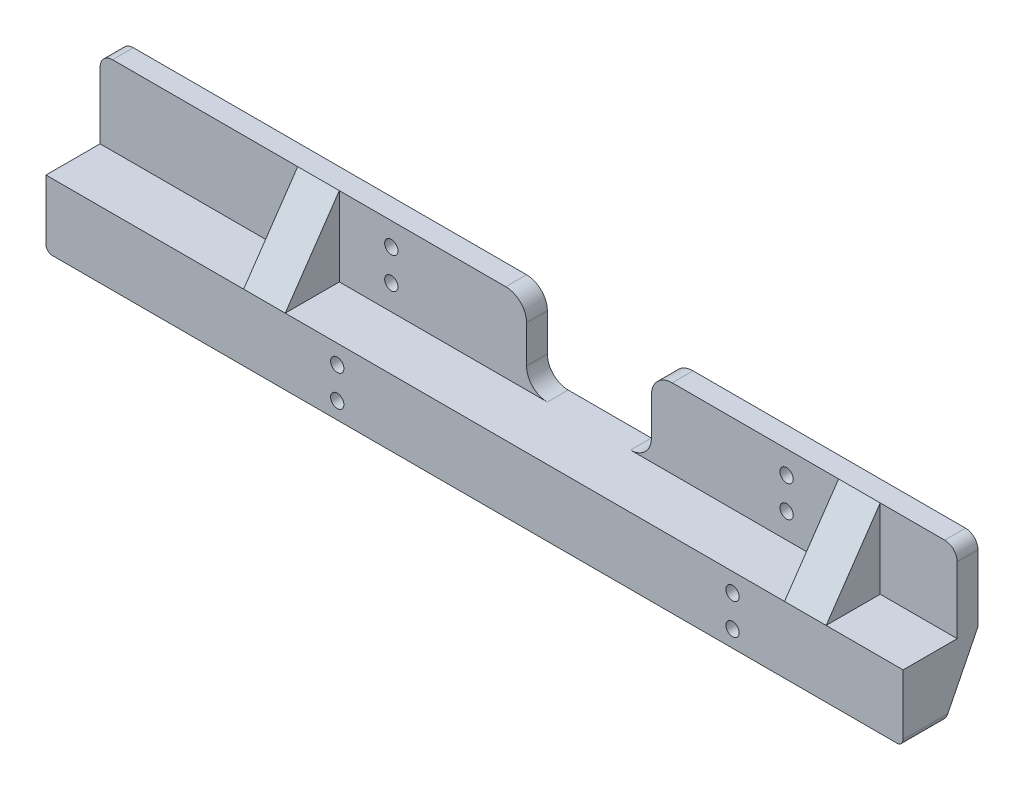
SolidWorks part; units mm, degrees
ref_plane "前视基准面" through (0, 0, 0) normal (0, 0, 1) x (1, 0, 0)
ref_plane "上视基准面" through (0, 0, 0) normal (0, 1, 0) x (1, 0, 0)
ref_plane "右视基准面" through (0, 0, 0) normal (1, 0, 0) x (0, 0, -1)
sketch "草图1" plane through (0, 0, 0) normal (0, 0, 1) x (1, 0, 0)
  line L1 (-117.5, 17.5) -> (117.5, 17.5)
  line L2 (-117.5, 17.5) -> (-117.5, -17.5)
  line L3 (-117.5, -17.5) -> (117.5, -17.5)
  line L4 (117.5, 17.5) -> (117.5, -17.5)
  line L5 (0, -17.5) -> (0, 17.5) construction
  line L6 (-117.5, 0) -> (117.5, 0) construction
  circle A1 centre (-47.5, 13.5) radius 1.6
  circle A2 centre (47.5, 13.5) radius 1.6
  circle A3 centre (-47.5, 6) radius 1.6
  circle A4 centre (47.5, 6) radius 1.6
  point P0 (0, 0)
  dimension "D1" = 95
  dimension "D4" = 4
  dimension "D5" = 3.2
  dimension "D6" = 7.5
  dimension "D2" = 35
  dimension "D3" = 235
extrude "凸台-拉伸1" add sketch "草图1" along normal blind 18
fillet "圆角1" radius 1.5 2 edges at (117.5, 17.5, 9) (-117.5, 17.5, 9)
sketch "草图2" plane through (-117.5, 0, 0) normal (-1, 0, 0) x (0, 0, 1)
  line L0 (0, 1.5) -> (8, 17.5)
  line L1 (0, 16) -> (0, -17.5) construction
  line L2 (0, 17.5) -> (18, 17.5) construction
  line L3 (8, 17.5) -> (0, 17.5)
  line L4 (0, 17.5) -> (0, 1.5)
  dimension "D1" = 16
  dimension "D2" = 8
extrude "切除-拉伸1" cut sketch "草图2" against normal through all
sketch "草图3" plane through (-117.5, 0, 0) normal (-1, 0, 0) x (0, 0, 1)
  line L0 (5, 1.5) -> (0, 1.5) construction
  line L1 (5, 1.5) -> (18, 1.5)
  line L3 (5, 1.5) -> (5, -17.5)
  line L4 (5, -17.5) -> (18, -17.5)
  line L5 (18, 1.5) -> (18, -17.5)
  dimension "D1" = 13
extrude "切除-拉伸2" cut sketch "草图3" against normal through all
sketch "草图5" plane through (0, 0, 0) normal (0, 0, -1) x (-1, 0, 0)
  line L0 (0, 0) -> (0, -50.6933) construction
  line L1 (-117.5, 1.5) -> (117.5, 1.5) construction
  line L2 (47.5, -12) -> (47.5, -4.5) construction
  line L3 (-47.5, -12) -> (-47.5, -4.5) construction
  circle A0 centre (47.5, -4.5) radius 1.6
  circle A1 centre (47.5, -12) radius 1.6
  circle A2 centre (-47.5, -12) radius 1.6
  circle A3 centre (-47.5, -4.5) radius 1.6
  dimension "D1" = 3.2
  dimension "D2" = 95
  dimension "D3" = 6
  dimension "D4" = 7.5
extrude "切除-拉伸5" cut sketch "草图5" against normal through all
sketch "草图6" plane through (0, 0, 0) normal (0, 0, -1) x (-1, 0, 0)
  circle A0 centre (47.5, 6) radius 3
  circle A1 centre (47.5, 13.5) radius 3
  circle A2 centre (-47.5, 6) radius 3
  circle A3 centre (-47.5, 13.5) radius 3
  dimension "D1" = 6
extrude "切除-拉伸6" cut sketch "草图6" against normal blind 10
sketch "草图7" plane through (0, 0, 5) normal (0, 0, 1) x (1, 0, 0)
  line L0 (117.5, -17.5) -> (-117.5, -17.5) construction
  line L1 (35, -7.5) -> (-35, -7.5)
  line L2 (35, -7.5) -> (35, -17.5)
  line L3 (35, -17.5) -> (-35, -17.5)
  line L4 (-35, -7.5) -> (-35, -17.5)
  line L5 (0, -17.5) -> (0, -7.5) construction
  line L6 (35, -12.5) -> (-35, -12.5) construction
  point P0 (0, -12.5)
  dimension "D1" = 70
  dimension "D2" = 10
extrude "切除-拉伸7" [suppressed] cut sketch "草图7" against normal through all
sketch "草图10" plane through (0, 0, 0) normal (0, 0, -1) x (-1, 0, 0)
  line L6 (117.5, -17.5) -> (-117.5, -17.5) construction
  line L7 (-88.5, -17.5) -> (-117.5, -17.5)
  line L8 (-88.5, -17.5) -> (-88.5, 17.5)
  line L9 (-88.5, 17.5) -> (-117.5, 17.5)
  line L10 (-117.5, -17.5) -> (-117.5, 17.5)
  line L11 (-116, 17.5) -> (116, 17.5) construction
  line L12 (-117.5, -17.5) -> (-117.5, 1.5) construction
  dimension "D1" = 29
extrude "切除-拉伸9" cut sketch "草图10" against normal blind 30
fillet "圆角2" radius 3 2 edges at (-117.5, -17.5, 2.5) (88.5, -17.5, 2.5)
fillet "圆角5" radius 1.5 1 edges at (88.5, 17.5, 13)
sketch "草图11" plane through (0, 0, 0) normal (0, 0, -1) x (-1, 0, 0)
  line L0 (114.5, -17.5) -> (-85.5, -17.5) construction
  line L1 (-15, -17.5) -> (15, -17.5)
  line L2 (-15, -17.5) -> (-15, 1.5)
  line L3 (-15, 1.5) -> (15, 1.5)
  line L4 (15, -17.5) -> (15, 1.5)
  line L5 (-88.5, 1.5) -> (117.5, 1.5) construction
  point P9 (0, -17.5)
  dimension "D1" = 30
extrude "切除-拉伸10" cut sketch "草图11" against normal blind 30
fillet "圆角6" radius 5 4 edges at (15, -17.5, 2.5) (-15, -17.5, 2.5) (15, 1.5, 2.5) (-15, 1.5, 2.5)
ref_plane "基准面1" through (60, 0, 0) normal (1, 0, 0) x (0, 0, -1)
sketch "草图12" plane through (60, 0, 0) normal (1, 0, 0) x (0, 0, -1)
  line L0 (-18, 1.5) -> (-5, -17.5)
  line L1 (-5, -17.5) -> (-5, 1.5)
  line L2 (-5, 1.5) -> (-18, 1.5)
extrude "凸台-拉伸2" add sketch "草图12" along normal blind 10
mirror "镜向1" about plane through (0, 0, 0) normal (1, 0, 0) of "凸台-拉伸2"
ref_plane "基准面2" through (0, -50, 0) normal (0, 1, 0) x (1, 0, 0)
mirror "镜向2" about plane through (0, -50, 0) normal (0, 1, 0) of bodies 120
sketch "草图13" plane through (0, 0, 0) normal (0, 0, -1) x (-1, 0, 0)
  line L1 (-111.3193, 49.9072) -> (138.6807, 49.9072)
  line L2 (-111.3193, 49.9072) -> (-111.3193, -38.0928)
  line L3 (-111.3193, -38.0928) -> (138.6807, -38.0928)
  line L4 (138.6807, 49.9072) -> (138.6807, -38.0928)
  dimension "D1" = 250
  dimension "D2" = 88
  dimension "D3" = 38.0928
  dimension "D4" = 138.6807
extrude "切除-拉伸11" cut sketch "草图13" against normal through all
